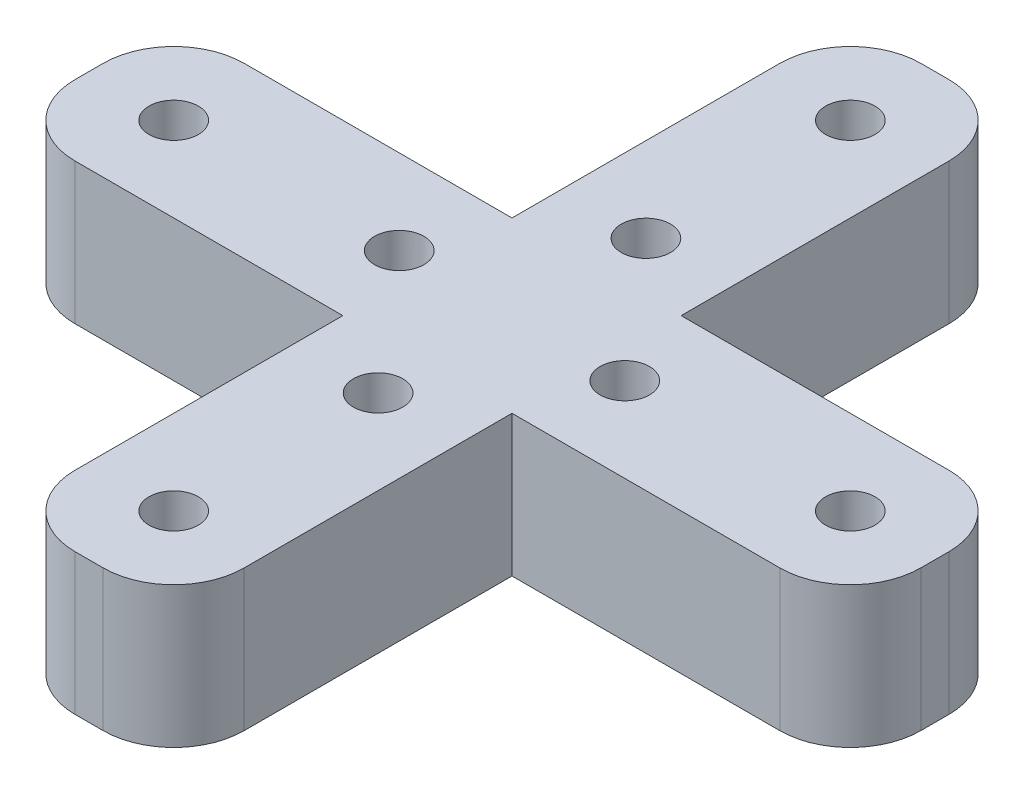
SolidWorks part; units mm, degrees
ref_plane "Front Plane" through (0, 0, 0) normal (0, 0, 1) x (1, 0, 0)
ref_plane "Top Plane" through (0, 0, 0) normal (0, 1, 0) x (1, 0, 0)
ref_plane "Right Plane" through (0, 0, 0) normal (1, 0, 0) x (0, 0, -1)
sketch "Sketch1" plane through (0, 0, 0) normal (0, 1, 0) x (1, 0, 0)
  line L0 (6, 6) -> (30, 6)
  line L1 (-6, -30) -> (6, -30)
  line L2 (-6, -30) -> (-6, -6)
  line L3 (-6, 30) -> (6, 30)
  line L4 (6, -30) -> (6, -6)
  line L7 (-30, 6) -> (-6, 6)
  line L8 (-30, 6) -> (-30, -6)
  line L9 (-30, -6) -> (-6, -6)
  line L10 (30, 6) -> (30, -6)
  line L17 (6, -6) -> (30, -6)
  line L18 (6, 6) -> (6, 30)
  line L19 (-6, 6) -> (-6, 30)
  point P0 (0, 0)
  point P6 (0, 0)
  dimension "D1" = 60
  dimension "D2" = 60
  dimension "D3" = 12
  dimension "D4" = 12
extrude "Boss-Extrude1" add sketch "Sketch1" along normal blind 10
fillet "Fillet1" radius 5 8 edges at (-6, 5, 30) (6, 5, 30) (30, 5, 6) (30, 5, -6) (6, 5, -30) (-6, 5, -30) (-30, 5, -6) (-30, 5, 6)
sketch "Sketch2" plane through (0, 10, 0) normal (0, 1, 0) x (1, 0, 0)
  line L0 (1, 30) -> (-1, 30) construction
  line L1 (-30, 1) -> (-30, -1) construction
  circle A0 centre (-8, 0) radius 1.75
  circle A1 centre (8, 0) radius 1.75
  circle A2 centre (0, 9.5) radius 1.75
  circle A3 centre (0, -9.5) radius 1.75
  point P10 (0, 30)
  point P13 (-30, 0)
  dimension "D1" = 3.5
  dimension "D2" = 3.5
  dimension "D3" = 3.5
  dimension "D4" = 3.5
  dimension "D5" = 19
  dimension "D6" = 16
  dimension "D7" = 20.5
  dimension "D8" = 22
extrude "Cut-Extrude1" cut sketch "Sketch2" against normal blind 15
sketch "Sketch3" plane through (0, 10, 0) normal (0, 1, 0) x (1, 0, 0)
  line L0 (-30, 1) -> (-30, -1) construction
  line L1 (1, 30) -> (-1, 30) construction
  line L2 (30, -1) -> (30, 1) construction
  line L3 (-1, -30) -> (1, -30) construction
  circle A0 centre (0, 24) radius 1.75
  circle A1 centre (24, 0) radius 1.75
  circle A2 centre (-24, 0) radius 1.75
  circle A3 centre (0, -24) radius 1.75
  dimension "D1" = 3.5
  dimension "D2" = 3.5
  dimension "D3" = 3.5
  dimension "D4" = 3.5
  dimension "D5" = 6
  dimension "D6" = 6
  dimension "D7" = 6
  dimension "D8" = 6
extrude "Cut-Extrude2" cut sketch "Sketch3" against normal blind 15
sketch "Sketch4" plane through (0, 0, 0) normal (0, -1, 0) x (1, 0, 0)
  circle A0 centre (0, -9.5) radius 3.25
  circle A1 centre (-8, 0) radius 3.25
  circle A2 centre (8, 0) radius 3.25
  circle A3 centre (0, 9.5) radius 3.25
  dimension "D1" = 6.5
  dimension "D2" = 6.5
  dimension "D3" = 6.5
  dimension "D4" = 6.5
extrude "Cut-Extrude3" cut sketch "Sketch4" against normal blind 3
